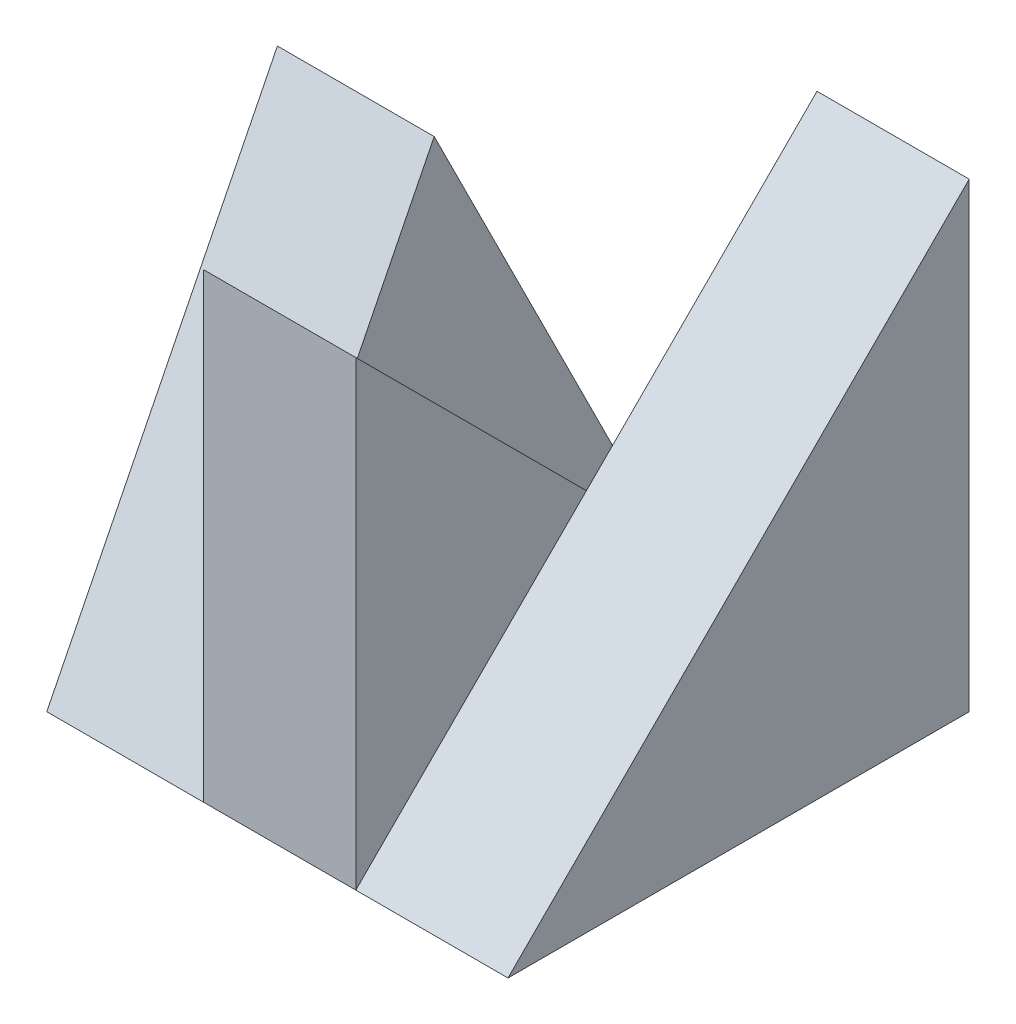
SolidWorks part; units mm, degrees
ref_plane "Front Plane" through (0, 0, 0) normal (0, 0, 1) x (1, 0, 0)
ref_plane "Top Plane" through (0, 0, 0) normal (0, 1, 0) x (1, 0, 0)
ref_plane "Right Plane" through (0, 0, 0) normal (1, 0, 0) x (0, 0, -1)
sketch "Sketch1" plane through (0, 0, 0) normal (0, 1, 0) x (1, 0, 0)
  line L1 (0, 0) -> (1, 0)
  line L2 (0, 0) -> (0, 1)
  line L3 (0, 1) -> (1, 1)
  line L4 (1, 0) -> (1, 1)
  dimension "D1" = 1
  dimension "D2" = 1
extrude "Boss-Extrude1" add sketch "Sketch1" along normal blind 1 contours L1 L4 L3 L2
sketch "Sketch2" plane through (1, 0, 0) normal (1, 0, 0) x (0, 0, -1)
  line L0 (0, 0) -> (1, 1)
extrude "Cut-Extrude1" cut sketch "Sketch2" against normal blind 0.33 and the other way through all
sketch "Sketch3" plane through (0.67, 0, 0) normal (1, 0, 0) x (0, 0, -1)
  line L0 (0, 1) -> (1, 0)
  line L1 (0, 1) -> (1, 1)
  line L2 (1, 1) -> (1, 0)
extrude "Cut-Extrude2" cut sketch "Sketch3" against normal blind 0.33
sketch "Sketch5" plane through (0, 0, 0) normal (-1, 0, 0) x (0, 0, 1)
  line L0 (-1, 0) -> (-0.5, 1)
  line L1 (0, 1) -> (-1, 1) construction
  line L2 (-0.5, 1) -> (0, 0)
extrude "Cut-Extrude3" cut sketch "Sketch5" against normal blind 0.34 and the other way through all
